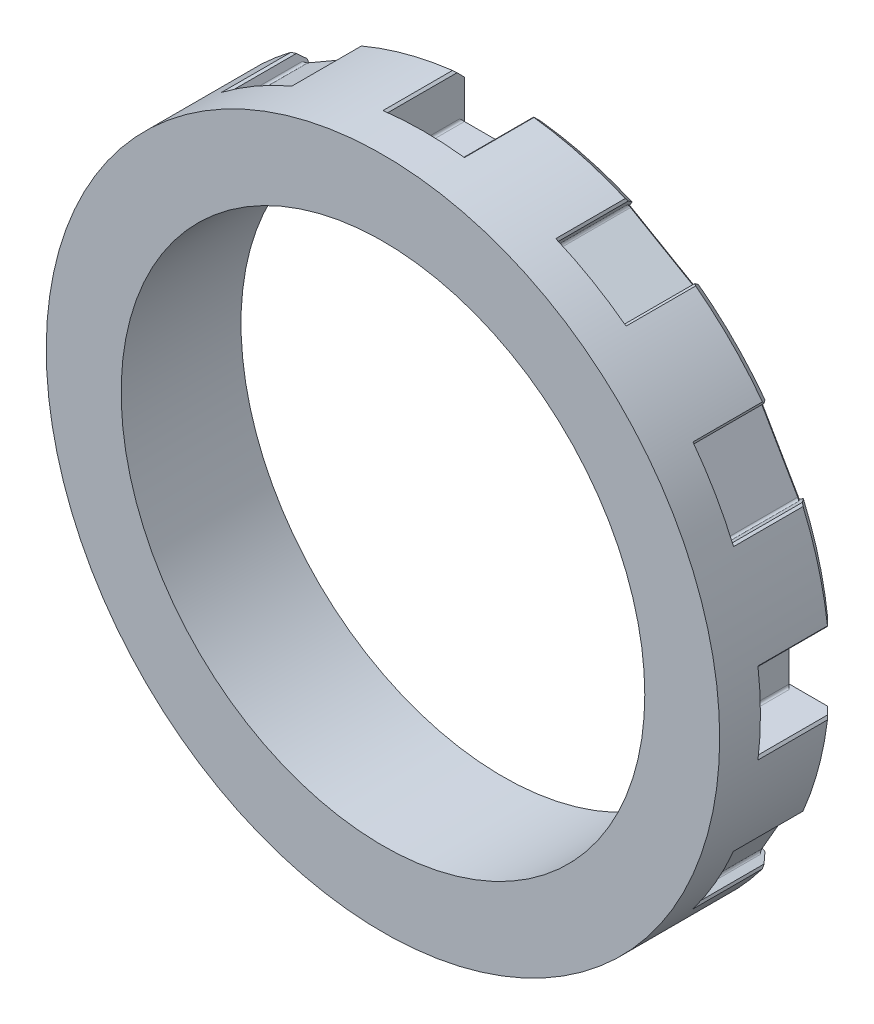
SolidWorks part; units mm, degrees
ref_plane "正面" through (0, 0, 0) normal (0, 0, 1) x (1, 0, 0)
ref_plane "平面" through (0, 0, 0) normal (0, 1, 0) x (1, 0, 0)
ref_plane "右側面" through (0, 0, 0) normal (1, 0, 0) x (0, 0, -1)
sketch "ｽｹｯﾁ1" plane through (0, 0, 0) normal (0, 0, 1) x (1, 0, 0)
  circle A0 centre (0, 0) radius 14.05
  dimension "D1" = 28.1
extrude "ﾎﾞｽ - 押し出し1" add sketch "ｽｹｯﾁ1" along normal blind 5
sketch "ｽｹｯﾁ2" plane through (0, 0, 5) normal (0, 0, 1) x (1, 0, 0)
  circle A0 centre (0, 0) radius 10.925
  dimension "D1" = 21.85
extrude "ｶｯﾄ - 押し出し1" cut sketch "ｽｹｯﾁ2" against normal through all
sketch "ｽｹｯﾁ3" plane through (0, 0, 0) normal (0, 0, 1) x (1, 0, 0)
  line L1 (1.6, 16.05) -> (-1.6, 16.05)
  line L2 (1.6, 16.05) -> (1.6, 12.05)
  line L3 (1.6, 12.05) -> (-1.6, 12.05)
  line L4 (-1.6, 16.05) -> (-1.6, 12.05)
  line L5 (1.6, 16.05) -> (-1.6, 12.05) construction
  line L6 (1.6, 12.05) -> (-1.6, 16.05) construction
  circle A0 centre (0, 0) radius 14.05 construction
  point P0 (0, 14.05)
  dimension "D1" = 3.2
  dimension "D2" = 2
extrude "ｶｯﾄ - 押し出し2" cut sketch "ｽｹｯﾁ3" along normal blind 3.3
pattern_circular "円形ﾊﾟﾀｰﾝ1" count 4 over 360 about axis through (0, 0, 0) along (0, 0, 1) of "ｶｯﾄ - 押し出し2"
sketch "ｽｹｯﾁ5" plane through (0, 0, 0) normal (0, 0, 1) x (1, 0, 0)
  line L0 (0, 0) -> (-25000, -43301.2702) construction
  line L1 (0, 0) -> (-35355.3391, -35355.3391) construction
  line L2 (0, 0) -> (0, -50000) construction
  line L3 (10.8555, 8.1149) -> (11.2885, 8.3649)
  line L4 (5.5937, 12.8885) -> (5.3437, 12.4555)
  line L5 (5.3437, 12.4555) -> (8.1149, 10.8555)
  line L6 (8.1149, 10.8555) -> (8.3649, 11.2885)
  line L7 (0.058, -0.0335) -> (43301.3282, -25000.0335) construction
  line L8 (12.4555, 5.3437) -> (10.8555, 8.1149)
  line L9 (12.8885, 5.5937) -> (12.4555, 5.3437)
  line L10 (0, 0) -> (35355.3391, -35355.3391) construction
  line L11 (-12.8885, -5.5937) -> (-12.4555, -5.3437)
  line L12 (-10.8555, -8.1149) -> (-11.2885, -8.3649)
  line L13 (-12.4555, -5.3437) -> (-10.8555, -8.1149)
  line L14 (-5.5937, -12.8885) -> (-5.3437, -12.4555)
  line L15 (-8.1149, -10.8555) -> (-8.3649, -11.2885)
  line L16 (-5.3437, -12.4555) -> (-8.1149, -10.8555)
  line L17 (-11.2885, 8.3649) -> (-10.8555, 8.1149)
  line L18 (-10.8555, 8.1149) -> (-12.4555, 5.3437)
  line L19 (-12.4555, 5.3437) -> (-12.8885, 5.5937)
  line L20 (-5.3437, 12.4555) -> (-5.5937, 12.8885)
  line L21 (-8.1149, 10.8555) -> (-5.3437, 12.4555)
  line L22 (-8.3649, 11.2885) -> (-8.1149, 10.8555)
  line L23 (11.2885, -8.3649) -> (10.8555, -8.1149)
  line L24 (10.8555, -8.1149) -> (12.4555, -5.3437)
  line L25 (12.4555, -5.3437) -> (12.8885, -5.5937)
  line L26 (8.3649, -11.2885) -> (8.1149, -10.8555)
  line L27 (8.1149, -10.8555) -> (5.3437, -12.4555)
  line L28 (5.3437, -12.4555) -> (5.5937, -12.8885)
  arc A0 (13.9586, 1.6) -> (1.6, 13.9586) centre (0, 0) ccw construction
  arc A1 (8.3649, 11.2885) -> (5.5937, 12.8885) centre (0, 0) ccw
  arc A2 (11.2885, 8.3649) -> (12.8885, 5.5937) centre (0, 0) cw
  arc A3 (-11.2885, -8.3649) -> (-12.8885, -5.5937) centre (0, 0) cw
  arc A4 (-8.3649, -11.2885) -> (-5.5937, -12.8885) centre (0, 0) ccw
  arc A5 (-1.6, 13.9586) -> (-13.9586, 1.6) centre (0, 0) ccw construction
  arc A6 (-11.2885, 8.3649) -> (-12.8885, 5.5937) centre (0, 0) ccw
  arc A7 (-8.3649, 11.2885) -> (-5.5937, 12.8885) centre (0, 0) cw
  arc A8 (11.2885, -8.3649) -> (12.8885, -5.5937) centre (0, 0) ccw
  arc A9 (8.3649, -11.2885) -> (5.5937, -12.8885) centre (0, 0) cw
  dimension "D1" = 30
  dimension "D2" = 60
  dimension "D3" = 3.2
  dimension "D4" = 0.5
  dimension "D5" = 45
  dimension "D6" = 45
  dimension "D7" = 3.2
  dimension "D8" = 0.5
extrude "ｶｯﾄ - 押し出し3" cut sketch "ｽｹｯﾁ5" along normal blind 3.3
chamfer "面取り1" distance 0.1 angle 45 36 edges at (11.2885, 8.3649, 1.65) (11.6555, 6.7293, 0) (12.8885, 5.5937, 1.65) (13.9586, 1.6, 1.65) (13.9586, -1.6, 1.65) (12.05, 0, 0) (12.8885, -5.5937, 1.65) (11.6555, -6.7293, 0) (11.2885, -8.3649, 1.65) (8.3649, -11.2885, 1.65) (6.7293, -11.6555, 0) (5.5937, -12.8885, 1.65) (1.6, -13.9586, 1.65) (0, -12.05, 0) (-1.6, -13.9586, 1.65) (-5.5937, -12.8885, 1.65) (-6.7293, -11.6555, 0) (-8.3649, -11.2885, 1.65) (-11.2885, -8.3649, 1.65) (-12.8885, -5.5937, 1.65) (-11.6555, -6.7293, 0) (-13.9586, 1.6, 1.65) (-12.05, 0, 0) (-13.9586, -1.6, 1.65) (-11.2885, 8.3649, 1.65) (-12.8885, 5.5937, 1.65) (-11.6555, 6.7293, 0) (-6.7293, 11.6555, 0) (-5.5937, 12.8885, 1.65) (-8.3649, 11.2885, 1.65) (0, 12.05, 0) (1.6, 13.9586, 1.65) (-1.6, 13.9586, 1.65) (8.3649, 11.2885, 1.65) (5.5937, 12.8885, 1.65) (6.7293, 11.6555, 0)
fillet "ﾌｨﾚｯﾄ1" radius 0.1 24 edges at (10.8555, 8.1149, 1.7) (12.4555, 5.3437, 1.7) (12.05, -1.6, 1.7) (12.05, 1.6, 1.7) (12.4555, -5.3437, 1.7) (10.8555, -8.1149, 1.7) (8.1149, -10.8555, 1.7) (5.3437, -12.4555, 1.7) (1.6, -12.05, 1.7) (-1.6, -12.05, 1.7) (-5.3437, -12.4555, 1.7) (-8.1149, -10.8555, 1.7) (-12.4555, -5.3437, 1.7) (-10.8555, -8.1149, 1.7) (-12.05, -1.6, 1.7) (-12.05, 1.6, 1.7) (-10.8555, 8.1149, 1.7) (-12.4555, 5.3437, 1.7) (-8.1149, 10.8555, 1.7) (-5.3437, 12.4555, 1.7) (1.6, 12.05, 1.7) (-1.6, 12.05, 1.7) (8.1149, 10.8555, 1.7) (5.3437, 12.4555, 1.7)
chamfer "面取り2" distance 0.4 angle 45 12 edges at (13.5713, 3.6364, 0) (13.57, -3.641, 0) (9.9315, -9.9382, 0) (3.6364, -13.5713, 0) (-3.641, -13.57, 0) (-9.9382, -9.9315, 0) (-13.5713, -3.6364, 0) (-13.57, 3.641, 0) (-9.9315, 9.9382, 0) (-3.6364, 13.5713, 0) (3.641, 13.57, 0) (9.9382, 9.9315, 0)
